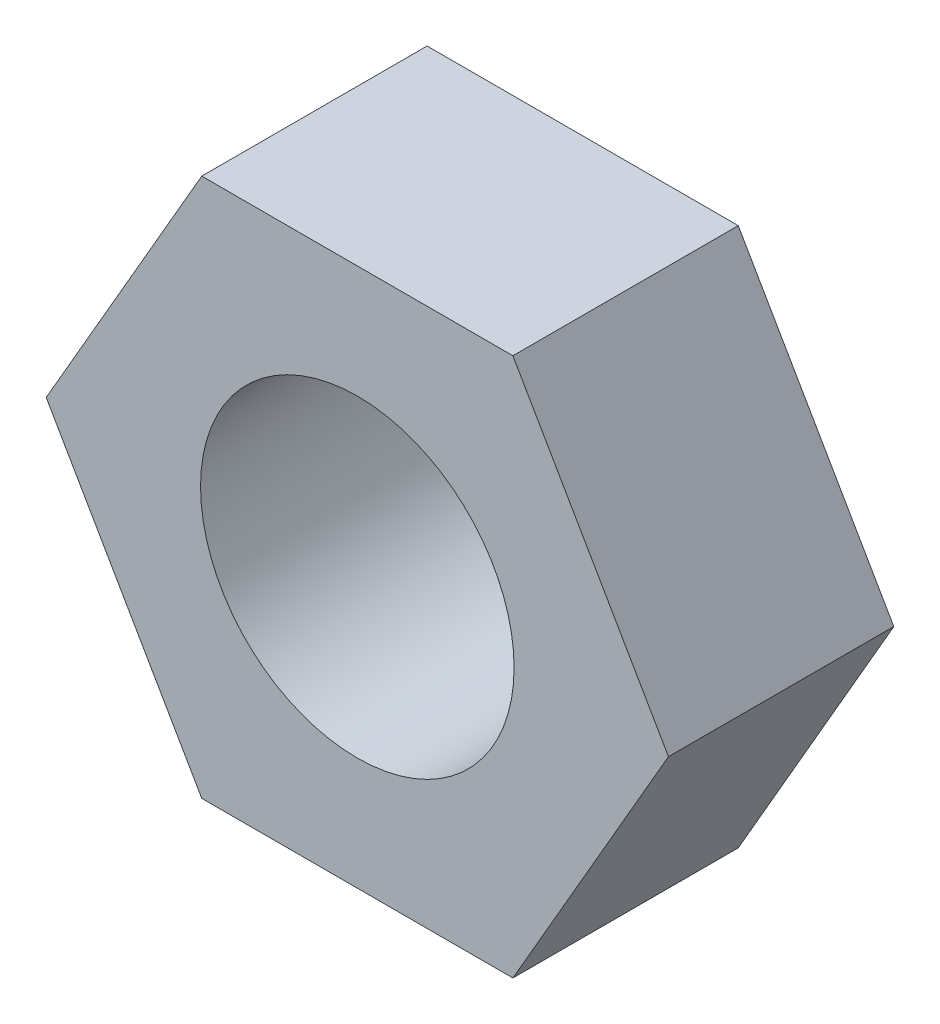
SolidWorks part; units mm, degrees
ref_plane "Plano frontal" through (0, 0, 0) normal (0, 0, 1) x (1, 0, 0)
ref_plane "Plano superior" through (0, 0, 0) normal (0, 1, 0) x (1, 0, 0)
ref_plane "Plano direito" through (0, 0, 0) normal (1, 0, 0) x (0, 0, -1)
sketch "Esboço1" plane through (0, 0, 0) normal (0, 0, 1) x (1, 0, 0)
  line L0 (0, 0) -> (0, 2.75) construction
  line L1 (1.5877, 2.75) -> (-1.5877, 2.75)
  line L2 (-1.5877, 2.75) -> (-3.1754, 0)
  line L3 (-3.1754, 0) -> (-1.5877, -2.75)
  line L4 (-1.5877, -2.75) -> (1.5877, -2.75)
  line L5 (1.5877, -2.75) -> (3.1754, 0)
  line L6 (3.1754, 0) -> (1.5877, 2.75)
  circle A0 centre (0, 0) radius 2.75 construction
  circle A1 centre (0, 0) radius 1.6
  point P10 (0.695, 3.0984)
  dimension "D2" = 3.2
  dimension "D1" = 5.5
extrude "Ressalto-extrusão1" add sketch "Esboço1" along normal blind 2.3
